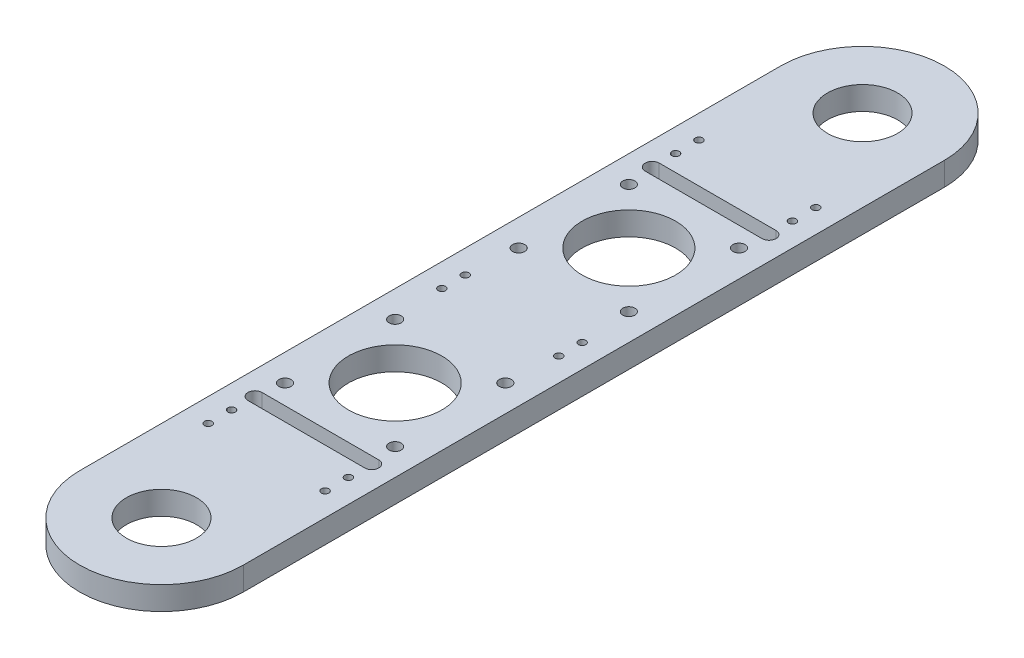
SolidWorks part; units mm, degrees
material "Acrylic (Medium-high impact)"
ref_plane "Front Plane" through (0, 0, 0) normal (0, 0, 1) x (1, 0, 0)
ref_plane "Top Plane" through (0, 0, 0) normal (0, 1, 0) x (1, 0, 0)
ref_plane "Right Plane" through (0, 0, 0) normal (1, 0, 0) x (0, 0, -1)
sketch "Sketch1" plane through (0, 0, 0) normal (0, 1, 0) x (1, 0, 0)
  line L0 (0, 150) -> (0, -150) construction
  line L1 (35, 150) -> (35, -150)
  line L2 (-35, 150) -> (-35, -150)
  arc A0 (35, 150) -> (-35, 150) centre (0, 150) ccw
  arc A1 (-35, -150) -> (35, -150) centre (0, -150) ccw
  circle A2 centre (0, -150) radius 15
  circle A3 centre (0, 150) radius 15
  point P2 (0, 0)
  dimension "D2" = 30
  dimension "D1" = 70
  dimension "D3" = 300
extrude "Boss-Extrude1" add sketch "Sketch1" along normal blind 10
sketch "Sketch2" plane through (0, 10, 0) normal (0, 1, 0) x (1, 0, 0)
  line L0 (-35, 0) -> (35, 0) construction
  line L1 (-35, 150) -> (-35, -150) construction
  line L2 (35, -150) -> (35, 150) construction
  line L3 (-25, 5) -> (-25, -5) construction
  line L4 (0, 0) -> (0, 50000) construction
  line L5 (25, 5) -> (25, -5) construction
  line L6 (-35, 100) -> (35, 100) construction
  line L7 (25, 105) -> (25, 95) construction
  line L8 (-25, 105) -> (-25, 95) construction
  line L9 (-25, -95) -> (-25, -105) construction
  line L10 (25, -95) -> (25, -105) construction
  line L11 (-35, -100) -> (35, -100) construction
  circle A0 centre (-25, 5) radius 1.6
  circle A1 centre (-25, -5) radius 1.6
  circle A2 centre (25, -5) radius 1.6
  circle A3 centre (25, 5) radius 1.6
  circle A4 centre (25, 95) radius 1.6
  circle A5 centre (25, 105) radius 1.6
  circle A6 centre (-25, 105) radius 1.6
  circle A7 centre (-25, 95) radius 1.6
  circle A8 centre (-25, -95) radius 1.6
  circle A9 centre (-25, -105) radius 1.6
  circle A10 centre (25, -105) radius 1.6
  circle A11 centre (25, -95) radius 1.6
  point P9 (-25, 0)
  point P13 (0, 0)
  point P25 (-25, 100)
  point P35 (-25, -100)
  dimension "D1" = 3.2
  dimension "D2" = 10
  dimension "D3" = 50
  dimension "D6" = 100
  dimension "D7" = 100
  dimension "D4" = 2
  dimension "D5" = 2
extrude "Cut-Extrude1" cut sketch "Sketch2" against normal through all both and the other way through all
sketch "Sketch3" plane through (0, 10, 0) normal (0, 1, 0) x (1, 0, 0)
  line L0 (-35, 0) -> (35, 0) construction
  line L1 (-35, 150) -> (-35, -150) construction
  line L2 (35, -150) -> (35, 150) construction
  line L4 (-25, -20) -> (25, -20)
  line L5 (-25, -20) -> (-25, -80)
  line L6 (-25, -80) -> (25, -80)
  line L7 (25, -20) -> (25, -80)
  dimension "D1" = 10
  dimension "D2" = 10
  dimension "D3" = 60
  dimension "10" = 20
extrude "Cut-Extrude2" [suppressed] cut sketch "Sketch3" against normal blind 10
fillet "Fillet1" [suppressed] radius 5
sketch "Sketch4" plane through (0, 0, 0) normal (0, -1, 0) x (1, 0, 0)
  line L0 (-35, -85) -> (35, -85) construction
  line L1 (-23.57, -73.57) -> (23.57, -73.57) construction
  line L2 (-23.57, -73.57) -> (-23.57, -26.43) construction
  line L3 (-23.57, -26.43) -> (23.57, -26.43) construction
  line L4 (23.57, -73.57) -> (23.57, -26.43) construction
  line L5 (-23.57, -73.57) -> (23.57, -26.43) construction
  line L6 (-23.57, -26.43) -> (23.57, -73.57) construction
  line L7 (-35, -150) -> (-35, 150) construction
  line L8 (35, 150) -> (35, -150) construction
  line L9 (-25, -85) -> (25, -85) construction
  line L10 (-25, -82) -> (25, -82)
  line L11 (-25, -88) -> (25, -88)
  circle A0 centre (0, -50) radius 20
  circle A1 centre (-23.57, -26.43) radius 2.6
  circle A2 centre (23.57, -26.43) radius 2.6
  circle A3 centre (23.57, -73.57) radius 2.6
  circle A4 centre (-23.57, -73.57) radius 2.6
  arc A5 (-25, -82) -> (-25, -88) centre (-25, -85) ccw
  arc A6 (25, -88) -> (25, -82) centre (25, -85) ccw
  point P0 (0, -50)
  point P20 (0, -85)
  point P25 (0, -85)
  dimension "D1" = 40
  dimension "D2" = 5.2
  dimension "D3" = 50
  dimension "D4" = 47.14
  dimension "D5" = 10
  dimension "D6" = 6
  dimension "D7" = 10
  dimension "D8" = 35
extrude "Cut-Extrude3" cut sketch "Sketch4" against normal through all
mirror "Mirror1" about plane through (0, 0, 0) normal (0, 0, 1) of "Cut-Extrude3"
